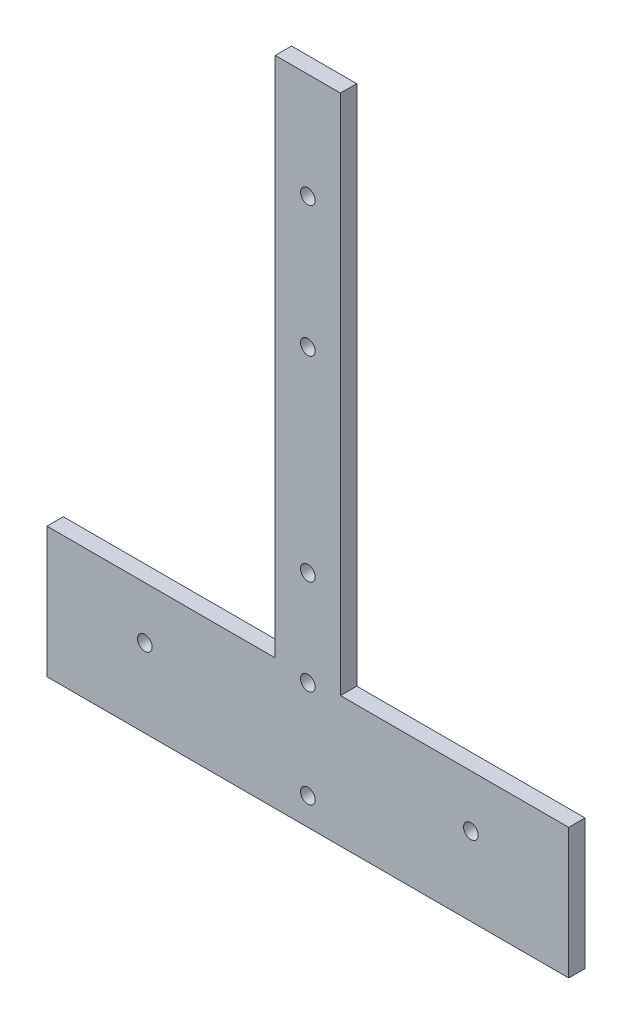
SolidWorks part; units mm, degrees
ref_plane "Front" through (0, 0, 0) normal (0, 0, 1) x (1, 0, 0)
ref_plane "Top" through (0, 0, 0) normal (0, 1, 0) x (1, 0, 0)
ref_plane "Right" through (0, 0, 0) normal (1, 0, 0) x (0, 0, -1)
sketch "Sketch1" plane through (0, 0, 0) normal (0, 0, 1) x (1, 0, 0)
  line L1 (10, -100) -> (-10, -100)
  line L2 (10, -100) -> (10, 100)
  line L3 (10, 100) -> (-10, 100)
  line L4 (-10, -100) -> (-10, 100)
  line L5 (10, -100) -> (-10, 100) construction
  line L6 (10, 100) -> (-10, -100) construction
  line L7 (-80, -100) -> (80, -100)
  line L8 (-80, -100) -> (-80, -60)
  line L9 (-80, -60) -> (80, -60)
  line L10 (80, -100) -> (80, -60)
  line L11 (-80, -100) -> (80, -60) construction
  line L12 (-80, -60) -> (80, -100) construction
  point P0 (0, 0)
  point P6 (0, -80)
  dimension "D1" = 20
  dimension "D2" = 200
  dimension "D3" = 0
  dimension "D4" = 160
  dimension "D5" = 10
  dimension "D6" = 40
extrude "Boss-Extrude1" add sketch "Sketch1" along normal blind 5 contours L4 L9 L2 L3 | L9 L4 L1 L2 | L9 L8 L7 L4 | L7 L10 L9 L2
sketch "Sketch2" plane through (0, 0, 5) normal (0, 0, 1) x (1, 0, 0)
  line L0 (-80, -100) -> (-80, -60) construction
  line L1 (80, -100) -> (-80, -100) construction
  line L2 (-10, -60) -> (-10, 100) construction
  line L3 (80, -100) -> (80, -60) construction
  line L5 (-80, -100) -> (-80, -60) construction
  circle A0 centre (0, -91.6) radius 2.25
  circle A1 centre (-50, -76) radius 2.25
  circle A2 centre (50, -76) radius 2.25
  circle A3 centre (0, 27.6) radius 2.25
  circle A4 centre (0, 67.6) radius 2.25
  circle A5 centre (0, -32.4) radius 2.25
  circle A6 centre (0, -61.6) radius 2.25
  dimension "D1" = 4.5
  dimension "D2" = 4.5
  dimension "D3" = 4.5
  dimension "D4" = 4.5
  dimension "D5" = 4.5
  dimension "D6" = 4.5
  dimension "D15" = 80
  dimension "D11" = 4.5
  dimension "D16" = 80
  dimension "D17" = 10
  dimension "D19" = 30
  dimension "D20" = 30
  dimension "D7" = 30
  dimension "D8" = 24
  dimension "D9" = 8.4
  dimension "D10" = 24
  dimension "D12" = 10
  dimension "D13" = 60
  dimension "D14" = 40
extrude "Cut-Extrude1" cut sketch "Sketch2" against normal blind 15
